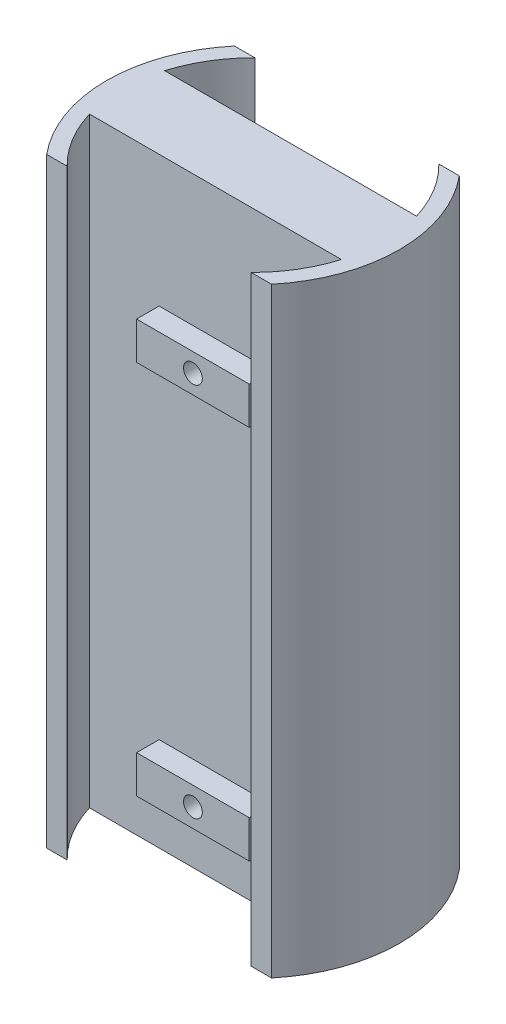
SolidWorks part; units mm, degrees
ref_plane "Front Plane" through (0, 0, 0) normal (0, 0, 1) x (1, 0, 0)
ref_plane "Top Plane" through (0, 0, 0) normal (0, 1, 0) x (1, 0, 0)
ref_plane "Right Plane" through (0, 0, 0) normal (1, 0, 0) x (0, 0, -1)
sketch "Sketch1" plane through (0, 0, 0) normal (0, 0, 1) x (1, 0, 0)
  line L1 (49.53, -101.6) -> (-49.53, -101.6)
  line L2 (49.53, -101.6) -> (49.53, 101.6)
  line L3 (49.53, 101.6) -> (-49.53, 101.6)
  line L4 (-49.53, -101.6) -> (-49.53, 101.6)
  line L5 (49.53, -101.6) -> (-49.53, 101.6) construction
  line L6 (49.53, 101.6) -> (-49.53, -101.6) construction
  point P0 (0, 0)
  dimension "D1" = 203.2
  dimension "D2" = 99.06
extrude "Boss-Extrude1" add sketch "Sketch1" along normal blind 25.4
sketch "Sketch2" plane through (0, 101.6, 0) normal (0, 1, 0) x (1, 0, 0)
  line L0 (-49.53, -12.7) -> (49.53, -12.7) construction
  line L1 (-49.53, -25.4) -> (-49.53, 0) construction
  line L2 (49.53, -25.4) -> (49.53, 0) construction
  line L3 (0, 0) -> (0, -25.4) construction
  line L4 (49.53, 0) -> (-49.53, 0) construction
  line L5 (49.53, -25.4) -> (-49.53, -25.4) construction
  circle A0 centre (0, -12.7) radius 49.53
  circle A1 centre (0, -12.7) radius 44.45
  dimension "D1" = 88.9
  dimension "D2" = 99.06
extrude "Boss-Extrude2" add sketch "Sketch2" against normal through all
sketch "Sketch3" plane through (0, 101.6, 0) normal (0, 1, 0) x (1, 0, 0)
  line L0 (-49.53, -12.7) -> (49.53, -12.7) construction
  line L1 (-49.53, -25.4) -> (-49.53, 0) construction
  line L2 (49.53, -25.4) -> (49.53, 0) construction
  line L3 (0, 0) -> (0, -25.4) construction
  line L4 (42.5971, -25.4) -> (-42.5971, -25.4) construction
  line L6 (-63.5, 19.05) -> (63.5, 19.05)
  line L7 (-63.5, 19.05) -> (-63.5, 44.45)
  line L8 (-63.5, 44.45) -> (63.5, 44.45)
  line L9 (63.5, 19.05) -> (63.5, 44.45)
  line L10 (-63.5, 19.05) -> (63.5, 44.45) construction
  line L11 (-63.5, 44.45) -> (63.5, 19.05) construction
  line L12 (-63.5, -69.85) -> (63.5, -69.85)
  line L13 (-63.5, -69.85) -> (-63.5, -44.45)
  line L14 (-63.5, -44.45) -> (63.5, -44.45)
  line L15 (63.5, -69.85) -> (63.5, -44.45)
  line L16 (-63.5, -69.85) -> (63.5, -44.45) construction
  line L17 (-63.5, -44.45) -> (63.5, -69.85) construction
  circle A0 centre (0, -12.7) radius 49.53
  circle A1 centre (0, -12.7) radius 57.15
  arc A2 (42.5971, 0) -> (-42.5971, 0) centre (0, -12.7) ccw construction
  arc A3 (-42.5971, -25.4) -> (42.5971, -25.4) centre (0, -12.7) ccw construction
  point P14 (0, 31.75)
  point P22 (0, -57.15)
  line M6 (-47.8741, 0) -> (-49.53, 0)
  line M7 (-49.53, 0) -> (-49.53, -25.4)
  line M8 (-49.53, -25.4) -> (-47.8741, -25.4)
  arc M9 (-47.8741, -25.4) -> (47.8741, -25.4) centre (0, -12.7) ccw
  line M10 (47.8741, -25.4) -> (49.53, -25.4)
  line M11 (49.53, -25.4) -> (49.53, 0)
  line M12 (49.53, 0) -> (47.8741, 0)
  arc M13 (47.8741, 0) -> (-47.8741, 0) centre (0, -12.7) ccw
  arc M15 (42.5971, -25.4) -> (-42.5971, -25.4) centre (0, -12.7) cw
  arc M16 (-42.5971, 0) -> (42.5971, 0) centre (0, -12.7) cw
  dimension "D1" = 99.06
  dimension "D2" = 114.3
  dimension "D3" = 25.4
  dimension "D4" = 127
  dimension "D5" = 25.4
  dimension "D6" = 127
extrude "Cut-Extrude1" cut sketch "Sketch3" against normal through all contours L6 A1 L14 M9 M8 M7 M6 M13 | L14 A1 L6 M13 M12 M11 M10 M9 | L6 M16 | L6 M13 M16 | L6 A1 M13 | A1 L8 L7 L6 | A1 L6 L9 L8 | A1 L12 L15 L14 | A1 L14 L13 L12 | A1 L14 M9 | L14 M9 M15 | L14 M15 | A0 M6 M7 | A0 M7 M8 | A0 M10 M11 | A0 M11 M12
sketch "Sketch6" plane through (0, 0, 25.4) normal (0, 0, 1) x (1, 0, 0)
  line L0 (0, -101.6) -> (0, 101.6) construction
  line L1 (38.0152, -101.6) -> (-38.0152, -101.6) construction
  line L2 (38.0152, -101.6) -> (38.0152, 101.6) construction
  line L3 (38.0152, 101.6) -> (-38.0152, 101.6) construction
  line L4 (-38.0152, -101.6) -> (-38.0152, 101.6) construction
  line L5 (38.0152, -101.6) -> (-38.0152, 101.6) construction
  line L6 (38.0152, 101.6) -> (-38.0152, -101.6) construction
  line L8 (-19.05, 44.45) -> (19.05, 44.45)
  line L9 (-19.05, 44.45) -> (-19.05, 57.15)
  line L10 (-19.05, 57.15) -> (19.05, 57.15)
  line L11 (19.05, 44.45) -> (19.05, 57.15)
  line L12 (-19.05, 44.45) -> (19.05, 57.15) construction
  line L13 (-19.05, 57.15) -> (19.05, 44.45) construction
  line L14 (-19.05, -82.55) -> (19.05, -82.55)
  line L15 (-19.05, -82.55) -> (-19.05, -69.85)
  line L16 (-19.05, -69.85) -> (19.05, -69.85)
  line L17 (19.05, -82.55) -> (19.05, -69.85)
  line L18 (-19.05, -82.55) -> (19.05, -69.85) construction
  line L19 (-19.05, -69.85) -> (19.05, -82.55) construction
  circle A0 centre (0, 50.8) radius 3.175
  circle A1 centre (0, -76.2) radius 3.175
  point P0 (0, 0)
  point P10 (0, 0)
  dimension "D1" = 6.35
  dimension "D2" = 6.35
  dimension "D3" = 127
  dimension "D4" = 76.2
  dimension "D5" = 12.7
  dimension "D6" = 38.1
  dimension "D7" = 38.1
  dimension "D8" = 12.7
extrude "Boss-Extrude3" add sketch "Sketch6" along normal blind 7.62
